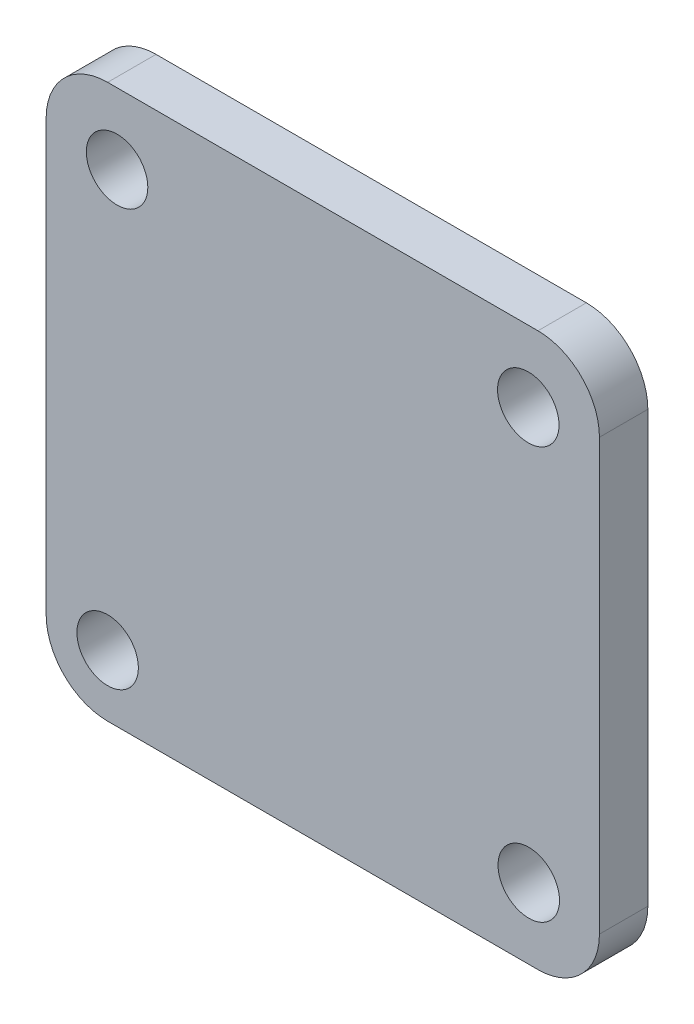
SolidWorks part; units mm, degrees
ref_plane "Front" through (0, 0, 0) normal (0, 0, 1) x (1, 0, 0)
ref_plane "Top" through (0, 0, 0) normal (0, 1, 0) x (1, 0, 0)
ref_plane "Right" through (0, 0, 0) normal (1, 0, 0) x (0, 0, -1)
sketch "Sketch1" plane through (0, 0, 0) normal (0, 0, 1) x (1, 0, 0)
  line L0 (1715.5834, -365.678) -> (1719.1688, -365.678) construction
  line L1 (1695.2634, -377.108) -> (1713.0434, -377.108)
  line L2 (1692.7234, -374.568) -> (1692.7234, -356.788)
  line L4 (1715.5834, -374.568) -> (1715.5834, -356.788)
  line L5 (1692.7234, -377.108) -> (1715.5834, -354.248) construction
  line L6 (1692.7234, -354.248) -> (1715.5834, -377.108) construction
  line L7 (1695.2634, -354.248) -> (1713.0434, -354.248)
  circle A0 centre (1695.6534, -357.1764) radius 1.27
  circle A1 centre (1712.6433, -357.188) radius 1.27
  circle A2 centre (1712.6635, -374.188) radius 1.27
  arc A4 (1695.2634, -377.108) -> (1692.7234, -374.568) centre (1695.2634, -374.568) cw
  arc A5 (1713.0434, -377.108) -> (1715.5834, -374.568) centre (1713.0434, -374.568) ccw
  arc A6 (1715.5834, -356.788) -> (1713.0434, -354.248) centre (1713.0434, -356.788) ccw
  arc A7 (1695.2634, -354.248) -> (1692.7234, -356.788) centre (1695.2634, -356.788) ccw
  circle A8 centre (1695.2634, -374.568) radius 1.27
  point P0 (1704.1534, -365.678)
  point P10 (1719.1688, -365.678)
  point P13 (1704.1534, -354.248)
  dimension "D3" = 2.54
  dimension "D1" = 22.86
  dimension "D2" = 22.86
extrude "Boss-Extrude1" add sketch "Sketch1" along normal blind 2
